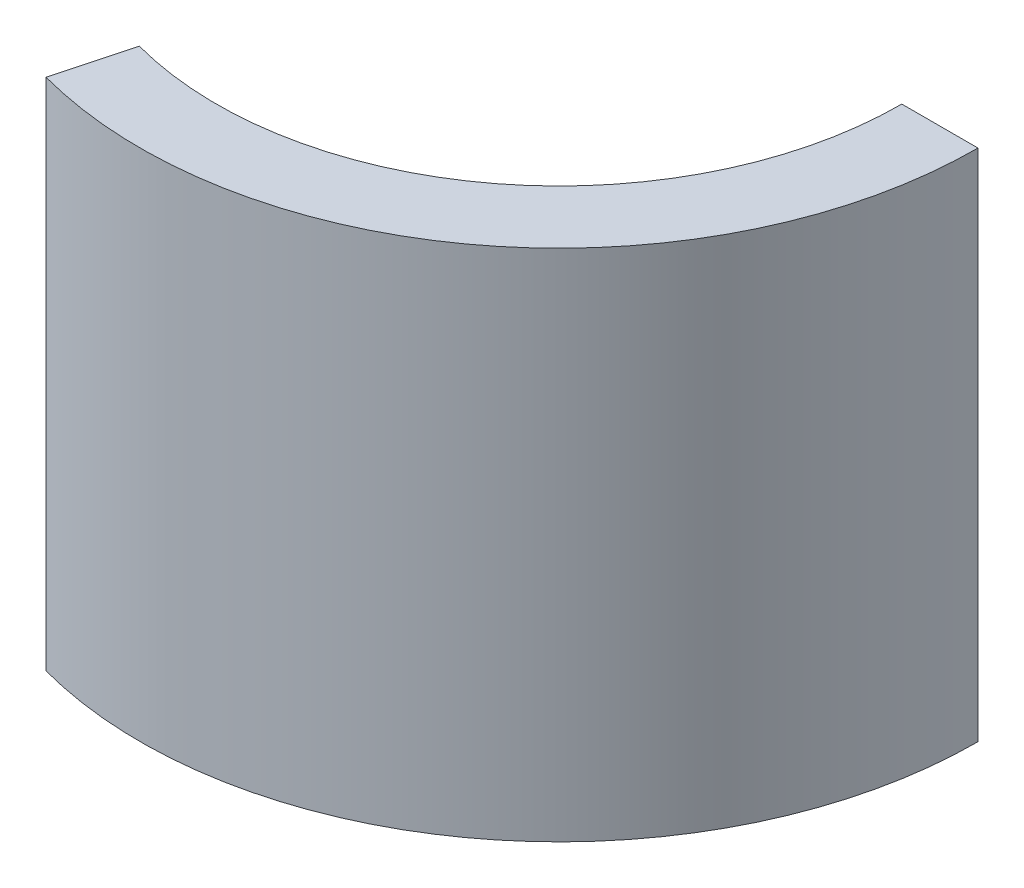
SolidWorks part; units mm, degrees
ref_plane "Front Plane" through (0, 0, 0) normal (0, 0, 1) x (1, 0, 0)
ref_plane "Top Plane" through (0, 0, 0) normal (0, 1, 0) x (1, 0, 0)
ref_plane "Right Plane" through (0, 0, 0) normal (1, 0, 0) x (0, 0, -1)
sketch "Sketch1" plane through (0, 0, 0) normal (0, 1, 0) x (1, 0, 0)
  line L2 (18, 0) -> (22, 0)
  line L3 (-4.6587, -17.3867) -> (-5.694, -21.2504)
  line L4 (0, 0) -> (-4.6587, -17.3867) construction
  arc A2 (-5.694, -21.2504) -> (22, 0) centre (0, 0) ccw
  arc A3 (-4.6587, -17.3867) -> (18, 0) centre (0, 0) ccw
  dimension "D2" = 4
  dimension "D3" = 105
  dimension "D1" = 44
extrude "Boss-Extrude1" add sketch "Sketch1" along normal blind 27
